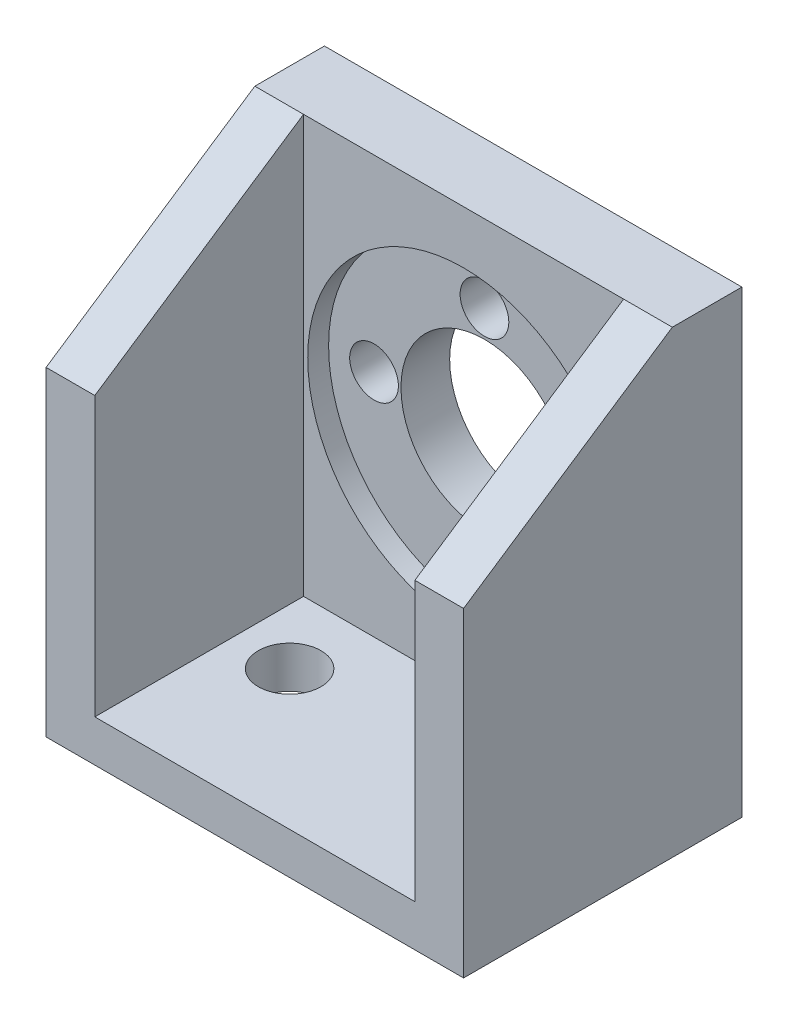
SolidWorks part; units mm, degrees
material "ABS"
ref_plane "Front Plane" through (0, 0, 0) normal (0, 0, 1) x (1, 0, 0)
ref_plane "Top Plane" through (0, 0, 0) normal (0, 1, 0) x (1, 0, 0)
ref_plane "Right Plane" through (0, 0, 0) normal (1, 0, 0) x (0, 0, -1)
sketch "Sketch1" plane through (0, 0, 0) normal (0, 0, 1) x (1, 0, 0)
  line L1 (-15, -16.5) -> (15, -16.5)
  line L2 (-15, -16.5) -> (-15, 16.5)
  line L3 (-15, 16.5) -> (15, 16.5)
  line L4 (15, -16.5) -> (15, 16.5)
  line L5 (-15, -16.5) -> (15, 16.5) construction
  line L6 (-15, 16.5) -> (15, -16.5) construction
  point P0 (0, 0)
  dimension "D1" = 30
  dimension "D2" = 33
extrude "Boss-Extrude1" add sketch "Sketch1" along normal blind 5
sketch "Sketch2" plane through (0, 0, 5) normal (0, 0, 1) x (1, 0, 0)
  line L0 (-15, 16.5) -> (-15, -16.5)
  line L1 (-15, -16.5) -> (15, -16.5)
  line L2 (15, -16.5) -> (15, 16.5)
  line L3 (15, 16.5) -> (11.5, 16.5)
  line L4 (15, 16.5) -> (-15, 16.5) construction
  line L5 (11.5, 16.5) -> (11.5, -13.5)
  line L6 (11.5, -13.5) -> (-11.5, -13.5)
  line L7 (-11.5, -13.5) -> (-11.5, 16.5)
  line L8 (-11.5, 16.5) -> (-15, 16.5)
  dimension "D1" = 3.5
  dimension "D2" = 3
extrude "Boss-Extrude2" add sketch "Sketch2" along normal blind 15
sketch "Sketch3" plane through (15, 0, 0) normal (1, 0, 0) x (0, 0, -1)
  line L0 (-5, 16.5) -> (-20, 16.5)
  line L1 (-20, 16.5) -> (0, 16.5) construction
  line L2 (-20, 16.5) -> (-20, 6.5)
  line L3 (-20, -16.5) -> (-20, 16.5) construction
  line L4 (-20, 6.5) -> (-5, 16.5)
  line L5 (0, -16.5) -> (0, 16.5) construction
  line L6 (-20, -16.5) -> (0, -16.5) construction
  dimension "D1" = 5
  dimension "D2" = 23
extrude "Cut-Extrude1" cut sketch "Sketch3" against normal through all
sketch "Sketch4" plane through (0, 0, 5) normal (0, 0, 1) x (1, 0, 0)
  line L0 (11.5, 16.5) -> (-11.5, 16.5) construction
  line L1 (0, 9.4341) -> (0, -6.434) construction
  line L2 (-7.9341, 1.5) -> (7.9341, 1.5) construction
  circle A0 centre (0, 1.5) radius 6
  circle A1 centre (0, 9.4341) radius 1.75
  circle A2 centre (-7.9341, 1.5) radius 1.75
  circle A3 centre (7.9341, 1.5) radius 1.75
  circle A4 centre (0, -6.434) radius 1.75
  dimension "D1" = 3.5
  dimension "D2" = 12
  dimension "D3" = 15
  dimension "D4" = 15.8681
  dimension "D5" = 15.8681
extrude "Cut-Extrude2" cut sketch "Sketch4" against normal through all
sketch "Sketch5" plane through (0, 0, 5) normal (0, 0, 1) x (1, 0, 0)
  circle A0 centre (0, 1.5) radius 11.1989
  dimension "D1" = 22.3978
extrude "Cut-Extrude3" cut sketch "Sketch5" against normal blind 1.5
sketch "Sketch6" plane through (0, -13.5, 0) normal (0, 1, 0) x (1, 0, 0)
  line L0 (-7.5, -10) -> (7.5, -10) construction
  line L1 (0, -10) -> (0, -5) construction
  line L2 (11.5, -5) -> (-11.5, -5) construction
  line L3 (11.5, -20) -> (-11.5, -20) construction
  circle A0 centre (-7.5, -10) radius 2.25
  circle A1 centre (7.5, -10) radius 2.25
  dimension "D1" = 4.5
  dimension "D2" = 10
  dimension "D3" = 15
extrude "Cut-Extrude4" cut sketch "Sketch6" against normal through all
